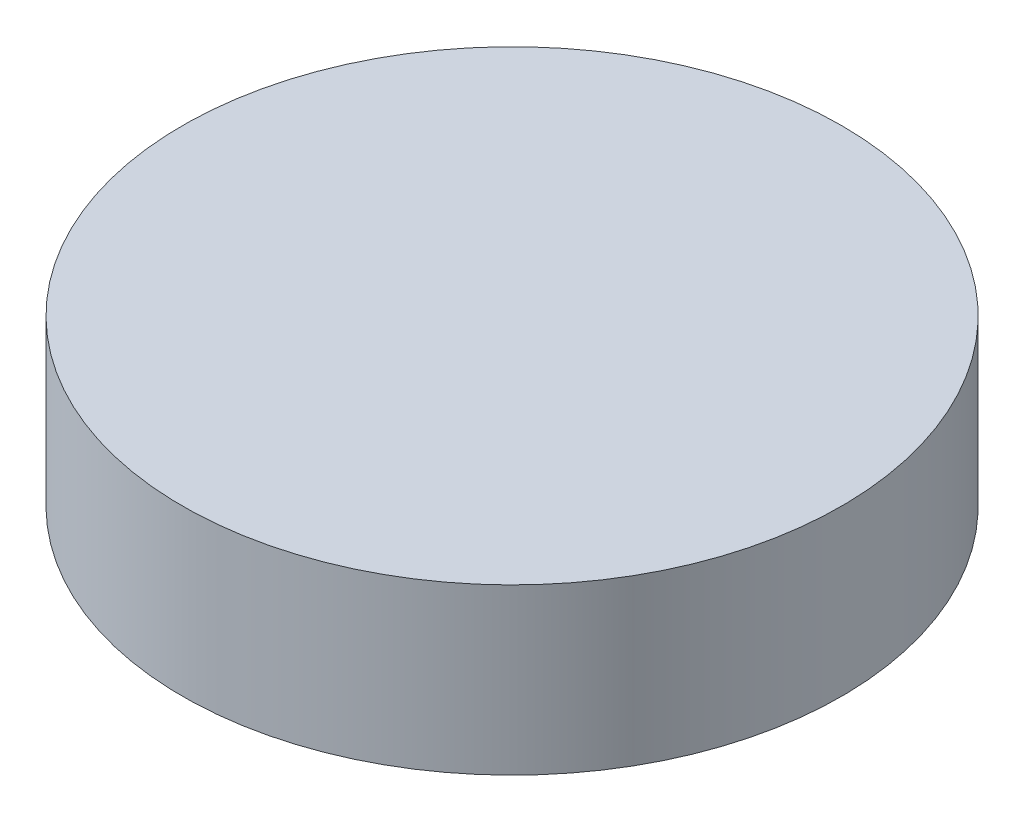
SolidWorks part; units mm, degrees
ref_plane "前视基准面" through (0, 0, 0) normal (0, 0, 1) x (1, 0, 0)
ref_plane "上视基准面" through (0, 0, 0) normal (0, 1, 0) x (1, 0, 0)
ref_plane "右视基准面" through (0, 0, 0) normal (1, 0, 0) x (0, 0, -1)
other "Configuration Table"
sketch "草图1" plane through (0, 0, 0) normal (0, 0, 1) x (1, 0, 0)
  line L0 (0, 0) -> (16, 0)
  line L1 (16, 0) -> (16, 8)
  line L2 (16, 8) -> (0, 8)
  line L3 (0, 8) -> (0, 0)
  line L4 (0, 0) -> (0, 8) construction
  dimension "radius" = 16
  dimension "height" = 8
revolve "Revolve" add sketch "草图1" angle 360 about L4
